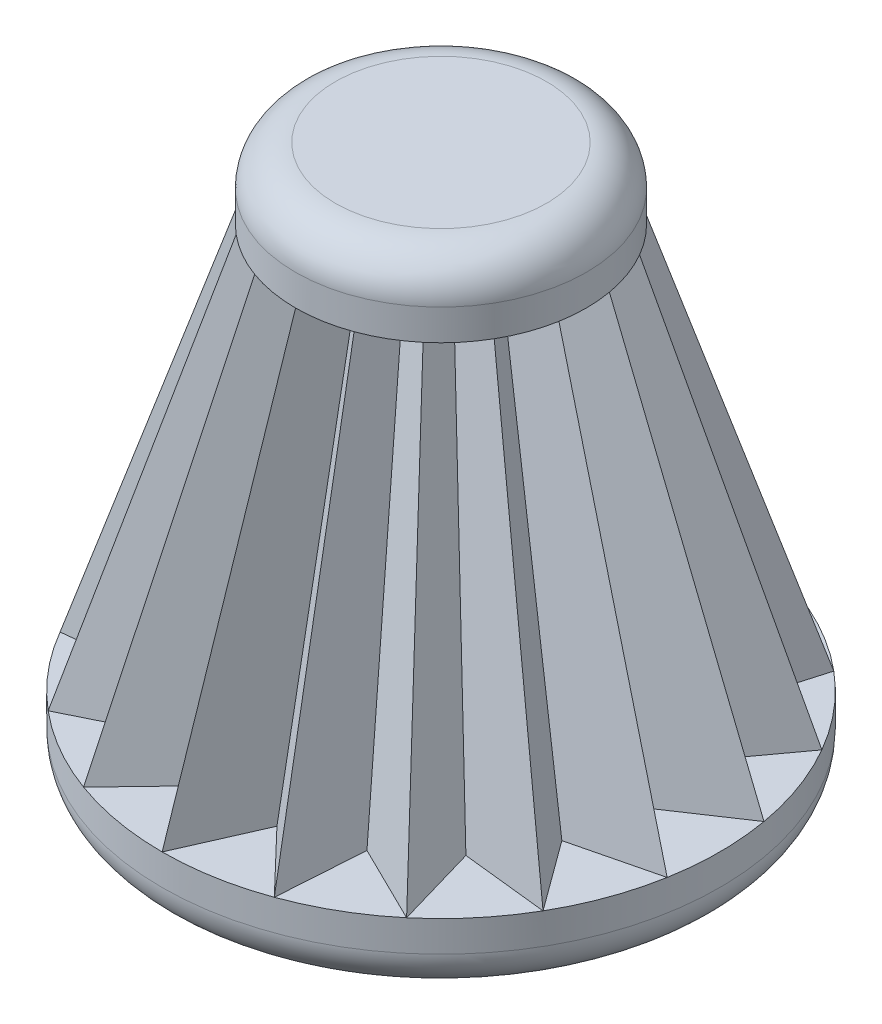
SolidWorks part; units mm, degrees
ref_plane "Front Plane" through (0, 0, 0) normal (0, 0, 1) x (1, 0, 0)
ref_plane "Top Plane" through (0, 0, 0) normal (0, 1, 0) x (1, 0, 0)
ref_plane "Right Plane" through (0, 0, 0) normal (1, 0, 0) x (0, 0, -1)
sketch "Sketch1" plane through (0, 0, 0) normal (0, 1, 0) x (1, 0, 0)
  line L0 (0, 0) -> (82.8306, 0) construction
  line L1 (0, 0) -> (0, 77.471) construction
  line L2 (0, 70) -> (-8.8163, 50)
  line L3 (0, 70) -> (8.8163, 50)
  line L4 (0, 0) -> (8.8163, 50) construction
  line L5 (23.9414, 65.7785) -> (8.8163, 50)
  line L6 (23.9414, 65.7785) -> (25.3857, 43.9693)
  line L7 (44.9951, 53.6231) -> (25.3857, 43.9693)
  line L8 (44.9951, 53.6231) -> (38.8931, 32.6352)
  line L9 (60.6218, 35) -> (38.8931, 32.6352)
  line L10 (60.6218, 35) -> (47.7094, 17.3648)
  line L11 (68.9365, 12.1554) -> (47.7094, 17.3648)
  line L12 (68.9365, 12.1554) -> (50.7713, 0)
  line L13 (68.9365, -12.1554) -> (50.7713, 0)
  line L14 (68.9365, -12.1554) -> (47.7094, -17.3648)
  line L15 (60.6218, -35) -> (47.7094, -17.3648)
  line L16 (60.6218, -35) -> (38.8931, -32.6352)
  line L17 (44.9951, -53.6231) -> (38.8931, -32.6352)
  line L18 (44.9951, -53.6231) -> (25.3857, -43.9693)
  line L19 (23.9414, -65.7785) -> (25.3857, -43.9693)
  line L20 (23.9414, -65.7785) -> (8.8163, -50)
  line L21 (0, -70) -> (8.8163, -50)
  line L22 (0, -70) -> (-8.8163, -50)
  line L23 (-23.9414, -65.7785) -> (-8.8163, -50)
  line L24 (-23.9414, -65.7785) -> (-25.3857, -43.9693)
  line L25 (-44.9951, -53.6231) -> (-25.3857, -43.9693)
  line L26 (-44.9951, -53.6231) -> (-38.8931, -32.6352)
  line L27 (-60.6218, -35) -> (-38.8931, -32.6352)
  line L28 (-60.6218, -35) -> (-47.7094, -17.3648)
  line L29 (-68.9365, -12.1554) -> (-47.7094, -17.3648)
  line L30 (-68.9365, -12.1554) -> (-50.7713, 0)
  line L31 (-68.9365, 12.1554) -> (-50.7713, 0)
  line L32 (-68.9365, 12.1554) -> (-47.7094, 17.3648)
  line L33 (-60.6218, 35) -> (-47.7094, 17.3648)
  line L34 (-60.6218, 35) -> (-38.8931, 32.6352)
  line L35 (-44.9951, 53.6231) -> (-38.8931, 32.6352)
  line L36 (-44.9951, 53.6231) -> (-25.3857, 43.9693)
  line L37 (-23.9414, 65.7785) -> (-25.3857, 43.9693)
  line L38 (-23.9414, 65.7785) -> (-8.8163, 50)
  point P61 (0, 0)
  dimension "D1" = 70
  dimension "D2" = 10
  dimension "D3" = 50
  dimension "D4" = 18
ref_plane "Plane1" through (0, 101.5, 0) normal (0, 1, 0) x (1, 0, 0)
sketch "Sketch2" plane through (0, 101.5, 0) normal (0, 1, 0) x (1, 0, 0)
  line L36 (-31.6099, -18.25) -> (-24.8771, -9.0545)
  line L37 (-35.9455, -6.3382) -> (-24.8771, -9.0545)
  line L38 (-35.9455, -6.3382) -> (-26.4736, 0)
  line L39 (-35.9455, 6.3382) -> (-26.4736, 0)
  line L40 (-35.9455, 6.3382) -> (-24.8771, 9.0545)
  line L41 (-31.6099, 18.25) -> (-24.8771, 9.0545)
  line L42 (-31.6099, 18.25) -> (-20.28, 17.0169)
  line L43 (-23.4617, 27.9606) -> (-20.28, 17.0169)
  line L44 (-23.4617, 27.9606) -> (-13.2368, 22.9268)
  line L45 (-12.4837, 34.2988) -> (-13.2368, 22.9268)
  line L46 (-12.4837, 34.2988) -> (-4.5971, 26.0714)
  line L47 (0, 36.5) -> (-4.5971, 26.0714)
  line L48 (0, 36.5) -> (4.5971, 26.0714)
  line L49 (12.4837, 34.2988) -> (4.5971, 26.0714)
  line L50 (12.4837, 34.2988) -> (13.2368, 22.9268)
  line L51 (23.4617, 27.9606) -> (13.2368, 22.9268)
  line L52 (23.4617, 27.9606) -> (20.28, 17.0169)
  line L53 (31.6099, 18.25) -> (20.28, 17.0169)
  line L54 (31.6099, 18.25) -> (24.8771, 9.0545)
  line L55 (35.9455, 6.3382) -> (24.8771, 9.0545)
  line L56 (35.9455, 6.3382) -> (26.4736, 0)
  line L57 (35.9455, -6.3382) -> (26.4736, 0)
  line L58 (35.9455, -6.3382) -> (24.8771, -9.0545)
  line L59 (31.6099, -18.25) -> (24.8771, -9.0545)
  line L60 (31.6099, -18.25) -> (20.28, -17.0169)
  line L61 (23.4617, -27.9606) -> (20.28, -17.0169)
  line L62 (23.4617, -27.9606) -> (13.2368, -22.9268)
  line L63 (12.4837, -34.2988) -> (13.2368, -22.9268)
  line L64 (12.4837, -34.2988) -> (4.5971, -26.0714)
  line L65 (0, -36.5) -> (4.5971, -26.0714)
  line L66 (0, -36.5) -> (-4.5971, -26.0714)
  line L67 (-12.4837, -34.2988) -> (-4.5971, -26.0714)
  line L68 (-12.4837, -34.2988) -> (-13.2368, -22.9268)
  line L69 (-23.4617, -27.9606) -> (-13.2368, -22.9268)
  line L70 (-23.4617, -27.9606) -> (-20.28, -17.0169)
  line L71 (-31.6099, -18.25) -> (-20.28, -17.0169)
  dimension "D1" = 36.5
  dimension "D2" = 4.5971
  dimension "D3" = 4.5971
  dimension "D4" = 12.4837
  dimension "D5" = 12.4837
  dimension "D6" = 13.2368
  dimension "D7" = 13.2368
  dimension "D8" = 20.28
  dimension "D9" = 20.28
  dimension "D10" = 23.4617
  dimension "D11" = 23.4617
  dimension "D12" = 24.8771
  dimension "D13" = 24.8771
  dimension "D14" = 26.4736
  dimension "D15" = 26.4736
  dimension "D16" = 31.6099
  dimension "D17" = 31.6099
  dimension "D18" = 35.9455
  dimension "D19" = 35.9455
  dimension "D20" = 4.5971
  dimension "D21" = 4.5971
  dimension "D22" = 12.4837
  dimension "D23" = 12.4837
  dimension "D24" = 13.2368
  dimension "D25" = 13.2368
  dimension "D26" = 20.28
  dimension "D27" = 20.28
  dimension "D28" = 23.4617
  dimension "D29" = 23.4617
  dimension "D30" = 24.8771
  dimension "D31" = 24.8771
  dimension "D32" = 6.3382
  dimension "D33" = 6.3382
  dimension "D34" = 31.6099
  dimension "D35" = 31.6099
  dimension "D36" = 35.9455
  dimension "D37" = 35.9455
  dimension "D38" = 9.0545
  dimension "D39" = 9.0545
  dimension "D40" = 17.0169
  dimension "D41" = 17.0169
  dimension "D42" = 18.25
  dimension "D43" = 18.25
  dimension "D44" = 22.9268
  dimension "D45" = 22.9268
  dimension "D46" = 26.0714
  dimension "D47" = 26.0714
  dimension "D48" = 27.9606
  dimension "D49" = 27.9606
  dimension "D50" = 34.2988
  dimension "D51" = 34.2988
  dimension "D52" = 36.5
  dimension "D53" = 36.5
  dimension "D54" = 6.3382
  dimension "D55" = 6.3382
  dimension "D56" = 9.0545
  dimension "D57" = 9.0545
  dimension "D58" = 17.0169
  dimension "D59" = 17.0169
  dimension "D60" = 18.25
  dimension "D61" = 18.25
  dimension "D62" = 22.9268
  dimension "D63" = 22.9268
  dimension "D64" = 26.0714
  dimension "D65" = 26.0714
  dimension "D66" = 27.9606
  dimension "D67" = 27.9606
  dimension "D68" = 34.2988
  dimension "D69" = 34.2988
loft "Loft1" add profiles "Sketch2", "Sketch1"
sketch "Sketch3" plane through (0, 101.5, 0) normal (0, 1, 0) x (1, 0, 0)
  circle A0 centre (0, 0) radius 36.5
shell "Shell2" thickness 1.01
extrude "Boss-Extrude3" add sketch "Sketch3" along normal blind 17.75 contours A0
sketch "Sketch5" plane through (0, 0, 0) normal (0, 1, 0) x (1, 0, 0)
  circle A0 centre (0, 0) radius 70
extrude "Boss-Extrude4" add sketch "Sketch5" against normal blind 17.75
fillet "Fillet3" radius 10 2 edges at (0, -17.75, 70) (0, 119.25, 36.5)
sketch "Sketch6" plane through (0, -17.75, 0) normal (0, -1, 0) x (1, 0, 0)
  circle A0 centre (0, 0) radius 15
  dimension "D1" = 30
extrude "Cut-Extrude1" cut sketch "Sketch6" against normal blind 57.75
